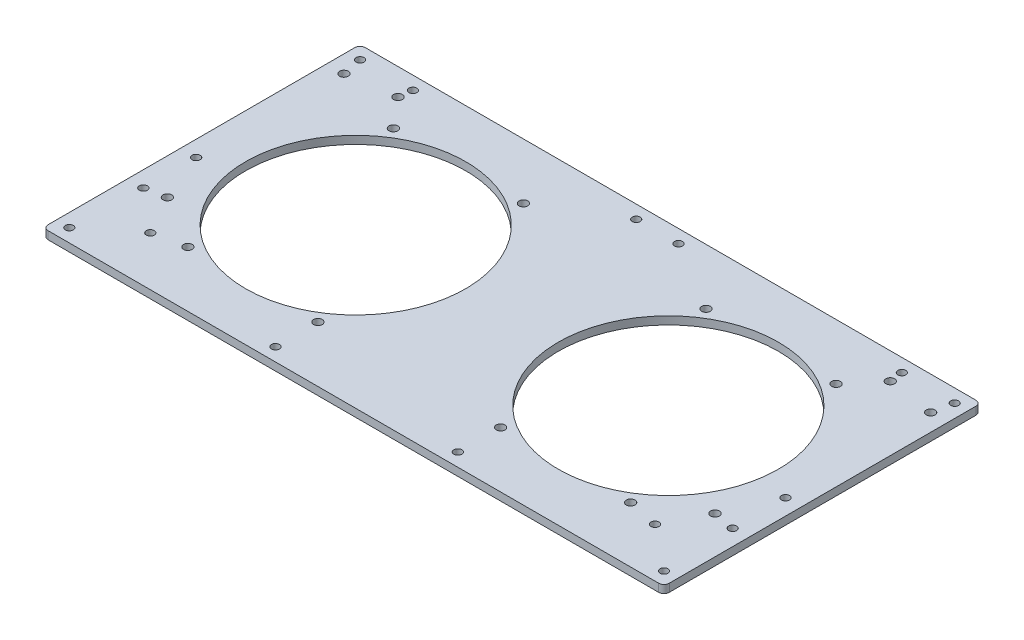
SolidWorks part; units mm, degrees
ref_plane "前视基准面" through (0, 0, 0) normal (0, 0, 1) x (1, 0, 0)
ref_plane "上视基准面" through (0, 0, 0) normal (0, 1, 0) x (1, 0, 0)
ref_plane "右视基准面" through (0, 0, 0) normal (1, 0, 0) x (0, 0, -1)
sketch "草图1" plane through (0, 0, 0) normal (0, 1, 0) x (1, 0, 0)
  line L0 (-17.5, 0) -> (0, 0) construction
  line L1 (-117.5, 60) -> (117.5, 60)
  line L2 (-117.5, 60) -> (-117.5, -60)
  line L3 (-117.5, -60) -> (117.5, -60)
  line L4 (117.5, 60) -> (117.5, -60)
  line L5 (-117.5, 60) -> (117.5, -60) construction
  line L6 (-117.5, -60) -> (117.5, 60) construction
  line L7 (0, 0) -> (0, 78.7988) construction
  circle A0 centre (-59.15, 0) radius 41.65
  circle A1 centre (59.15, 0) radius 41.65
  point P0 (0, 0)
  dimension "D3" = 83.3
  dimension "D4" = 17.5
  dimension "D1" = 235
  dimension "D2" = 120
extrude "凸台-拉伸1" add sketch "草图1" along normal blind 3
sketch "草图2" plane through (0, 3, 0) normal (0, 1, 0) x (1, 0, 0)
  line L0 (-59.15, 0) -> (-59.15, 18.4943) construction
  line L1 (0, 0) -> (0, 13.9098) construction
  circle A8 centre (-59.15, 0) radius 46 construction
  circle A9 centre (-83.75, -38.8695) radius 1.65
  circle A10 centre (-83.75, 38.8695) radius 1.65
  circle A11 centre (-34.55, 38.8695) radius 1.65
  circle A12 centre (-34.55, -38.8695) radius 1.65
  circle A13 centre (34.55, -38.8695) radius 1.65
  circle A14 centre (83.75, -38.8695) radius 1.65
  circle A15 centre (34.55, 38.8695) radius 1.65
  circle A16 centre (83.75, 38.8695) radius 1.65
  dimension "D1" = 92
  dimension "D3" = 24.6
  dimension "D2" = 3.3
  dimension "D4" = 24.6
  dimension "D5" = 3.3
extrude "切除-拉伸1" cut sketch "草图2" against normal blind 3
sketch "草图3" plane through (0, 3, 0) normal (0, 1, 0) x (1, 0, 0)
  line L0 (-117.5, 60) -> (-117.5, -60) construction
  line L1 (-117.5, -60) -> (117.5, -60) construction
  line L2 (0, 0) -> (0, -72.8657) construction
  line L3 (117.5, 60) -> (-117.5, 60) construction
  circle A0 centre (-111.5, -28) radius 1.5
  circle A1 centre (-111.5, -8) radius 1.5
  circle A2 centre (111.5, -8) radius 1.5
  circle A3 centre (111.5, -28) radius 1.5
  circle A4 centre (-112.5, 55) radius 1.5
  circle A5 centre (-92.5, 55) radius 1.5
  circle A6 centre (92.5, 55) radius 1.5
  circle A7 centre (112.5, 55) radius 1.5
  arc A8 (-111.5, -28) -> (-110.0011, -27.9437) centre (-111.5, -8) cw construction
  arc A9 (111.5, -28) -> (110.5, -27.975) centre (111.5, -8) ccw construction
  circle A10 centre (103.31, -26.5) radius 1.65
  arc A11 (-112.5, 55) -> (-112.4987, 55.2294) centre (-92.5, 55) cw construction
  arc A12 (-112.4987, 55.2294) -> (-112.1998, 58.452) centre (-92.5, 55) ccw construction
  arc A13 (-92.5, 55) -> (-92.6045, 57.0421) centre (-112.5, 55) cw construction
  circle A15 centre (-93.1351, 50) radius 1.65
  circle A16 centre (-111, 47.4007) radius 1.65
  circle A17 centre (93.1351, 50) radius 1.65
  circle A18 centre (111, 47.4007) radius 1.65
  circle A19 centre (-111.5, -28) radius 20 construction
  circle A20 centre (-95.4856, -41.3748) radius 1.5
  circle A21 centre (-83.75, -38.8695) radius 1.65 construction
  circle A22 centre (95.4856, -41.3748) radius 1.5
  dimension "D1" = 3
  dimension "D2" = 6
  dimension "D3" = 32
  dimension "D4" = 3
  dimension "D5" = 20
  dimension "D6" = 3
  dimension "D7" = 5
  dimension "D8" = 5
  dimension "D9" = 3
  dimension "D10" = 20
  dimension "D12" = 10
  dimension "D14" = 18.5
  dimension "D17" = 12
  dimension "D11" = 18.5
  dimension "D13" = 20
  dimension "D15" = 20
  dimension "D16" = 6
extrude "切除-拉伸2" cut sketch "草图3" against normal blind 3
sketch "草图4" plane through (0, 3, 0) normal (0, 1, 0) x (1, 0, 0)
  line L0 (-117.5, 60) -> (-117.5, -60) construction
  line L1 (-117.5, -60) -> (117.5, -60) construction
  line L2 (117.5, 60) -> (-117.5, 60) construction
  line L3 (117.5, -60) -> (117.5, 60) construction
  circle A0 centre (-112.5, -55) radius 1.5
  circle A1 centre (-112.5, 55) radius 1.5
  circle A2 centre (112.5, 55) radius 1.5
  circle A3 centre (112.5, -55) radius 1.5
  circle A4 centre (-34.5, -55) radius 1.5
  circle A5 centre (34.5, -55) radius 1.5
  dimension "D1" = 3
  dimension "D2" = 5
  dimension "D3" = 5
  dimension "D4" = 3
  dimension "D5" = 5
  dimension "D6" = 5
  dimension "D7" = 3
  dimension "D8" = 5
  dimension "D9" = 5
  dimension "D10" = 3
  dimension "D11" = 3
  dimension "D12" = 78
  dimension "D13" = 3
  dimension "D14" = 78
  dimension "D15" = 5
  dimension "D16" = 5
  dimension "D17" = 5
  dimension "D18" = 5
extrude "切除-拉伸3" cut sketch "草图4" against normal blind 3
sketch "草图5" plane through (0, 3, 0) normal (0, 1, 0) x (1, 0, 0)
  line L0 (117.5, 60) -> (-117.5, 60) construction
  circle A0 centre (-8, 55) radius 1.5
  circle A1 centre (8, 55) radius 1.5
  dimension "D1" = 3
  dimension "D2" = 5
  dimension "D3" = 8
  dimension "D4" = 3
  dimension "D5" = 5
  dimension "D6" = 8
extrude "切除-拉伸4" cut sketch "草图5" against normal blind 3
fillet "圆角1" radius 2 4 edges at (-117.5, 1.5, -60) (-117.5, 1.5, 60) (117.5, 1.5, 60) (117.5, 1.5, -60)
sketch "草图6" plane through (0, 3, 0) normal (0, 1, 0) x (1, 0, 0)
  line L1 (0, 0) -> (0, -68.2323) construction
  arc A0 (-111.5, -28) -> (-111.4394, -27.9999) centre (-111.5, -8) cw construction
  circle A1 centre (-103.9007, -26.5) radius 1.65
  dimension "D1" = 18.5
extrude "切除-拉伸5" cut sketch "草图6" against normal blind 10 contours A1
